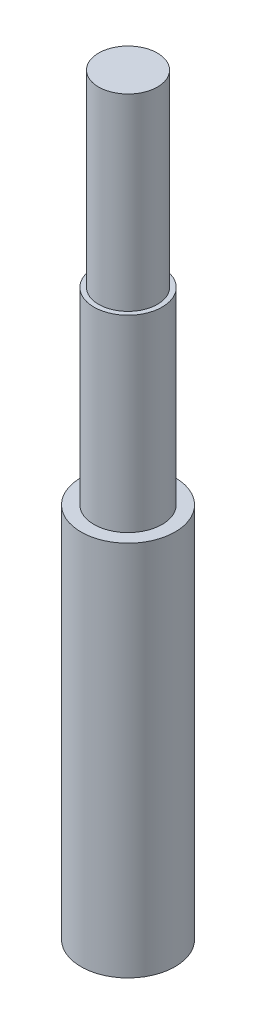
SolidWorks part; units mm, degrees
material "PUR"
ref_plane "Z" through (0, 0, 0) normal (0, 0, 1) x (1, 0, 0)
ref_plane "Y" through (0, 0, 0) normal (0, 1, 0) x (1, 0, 0)
ref_plane "X" through (0, 0, 0) normal (1, 0, 0) x (0, 0, -1)
sketch "Sketch1" plane through (0, 0, 0) normal (0, 1, 0) x (1, 0, 0)
  circle A0 centre (0, 0) radius 3.175
  dimension "D1" = 6.35
extrude "Boss-Extrude1" add sketch "Sketch1" along normal blind 38.1
sketch "Sketch2" plane through (0, 38.1, 0) normal (0, 1, 0) x (1, 0, 0)
  circle A0 centre (0, 0) radius 2.3
  circle A1 centre (0, 0) radius 3.5913
  dimension "D1" = 4.6
extrude "Cut-Extrude1" cut sketch "Sketch2" against normal blind 12.7
sketch "Sketch3" plane through (0, 38.1, 0) normal (0, 1, 0) x (1, 0, 0)
  circle A0 centre (0, 0) radius 1.9844
  dimension "D1" = 3.9688
extrude "Boss-Extrude2" add sketch "Sketch3" along normal blind 12.7
